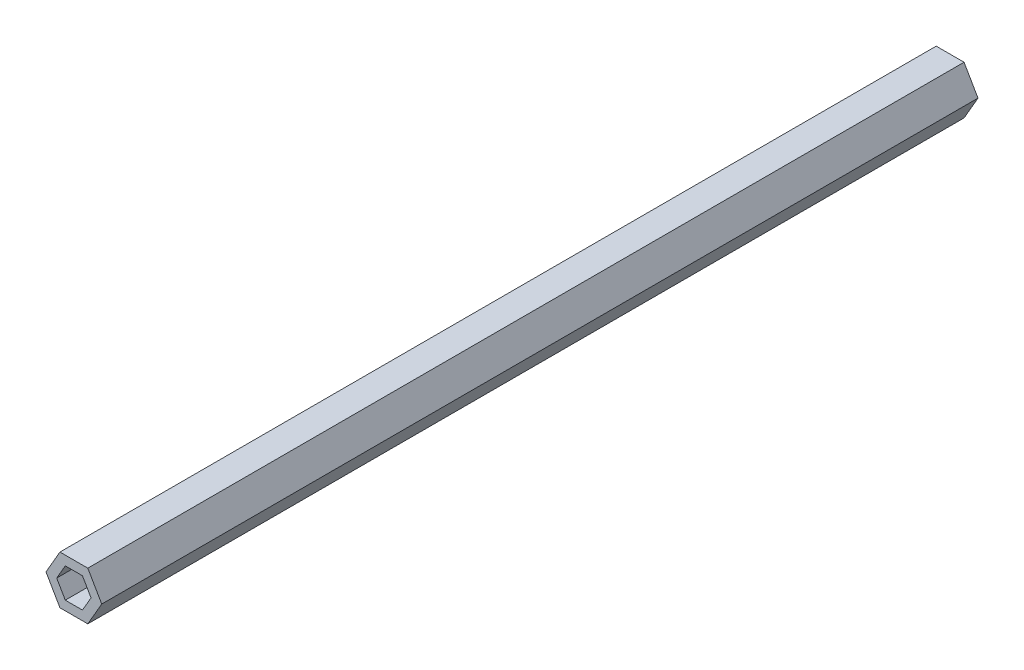
SolidWorks part; units mm, degrees
ref_plane "Front Plane" through (0, 0, 0) normal (0, 0, 1) x (1, 0, 0)
ref_plane "Top Plane" through (0, 0, 0) normal (0, 1, 0) x (1, 0, 0)
ref_plane "Right Plane" through (0, 0, 0) normal (1, 0, 0) x (0, 0, -1)
sketch "Sketch1" plane through (0, 0, 0) normal (0, 0, 1) x (1, 0, 0)
  line L1 (5.715, 0) -> (2.8575, 4.9493)
  line L2 (2.8575, 4.9493) -> (-2.8575, 4.9493)
  line L3 (-2.8575, 4.9493) -> (-5.715, 0)
  line L4 (-5.715, 0) -> (-2.8575, -4.9493)
  line L5 (-2.8575, -4.9493) -> (2.8575, -4.9493)
  line L6 (2.8575, -4.9493) -> (5.715, 0)
  circle A0 centre (0, 0) radius 4.9493 construction
  dimension "D1" = 11.43
extrude "Boss-Extrude1" add sketch "Sketch1" along normal blind 179.705
sketch "Sketch2" plane through (0, 0, 179.705) normal (0, 0, 1) x (1, 0, 0)
  line L1 (3.5218, 0) -> (1.7609, 3.05)
  line L2 (1.7609, 3.05) -> (-1.7609, 3.05)
  line L3 (-1.7609, 3.05) -> (-3.5218, 0)
  line L4 (-3.5218, 0) -> (-1.7609, -3.05)
  line L5 (-1.7609, -3.05) -> (1.7609, -3.05)
  line L6 (1.7609, -3.05) -> (3.5218, 0)
  circle A0 centre (0, 0) radius 3.05 construction
  dimension "D1" = 6.1
extrude "Cut-Extrude1" cut sketch "Sketch2" against normal blind 6.35
sketch "Sketch3" plane through (0, 0, 0) normal (0, 0, -1) x (-1, 0, 0)
  line L1 (1.7609, 3.05) -> (-1.7609, 3.05)
  line L2 (-1.7609, 3.05) -> (-3.5218, 0)
  line L3 (-3.5218, 0) -> (-1.7609, -3.05)
  line L4 (-1.7609, -3.05) -> (1.7609, -3.05)
  line L5 (1.7609, -3.05) -> (3.5218, 0)
  line L6 (3.5218, 0) -> (1.7609, 3.05)
  circle A0 centre (0, 0) radius 3.05 construction
  dimension "D1" = 6.1
extrude "Cut-Extrude2" cut sketch "Sketch3" against normal blind 6.35
equation "\"D1@Sketch3\"=6mm+.1mm"
equation "\"D1@Sketch2\"=6mm+.1mm"
